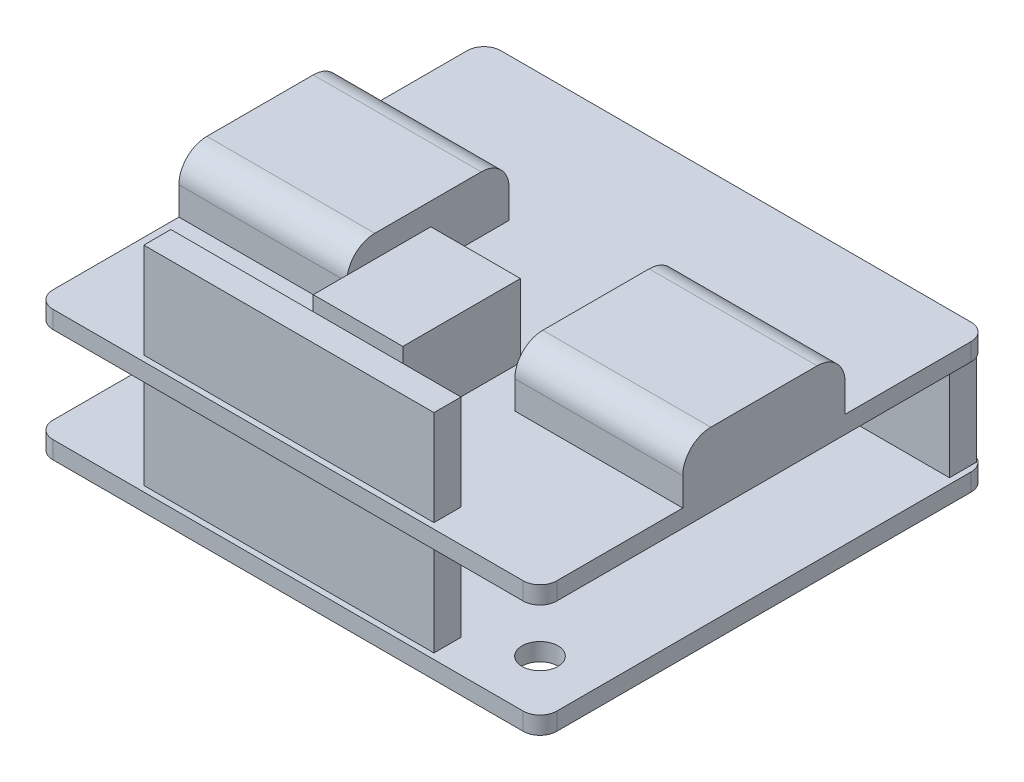
SolidWorks part; units mm, degrees
ref_plane "Front Plane" through (0, 0, 0) normal (0, 0, 1) x (1, 0, 0)
ref_plane "Top Plane" through (0, 0, 0) normal (0, 1, 0) x (1, 0, 0)
ref_plane "Right Plane" through (0, 0, 0) normal (1, 0, 0) x (0, 0, -1)
sketch "Sketch1" plane through (0, 0, 0) normal (0, 1, 0) x (1, 0, 0)
  line L1 (-22.5, -20) -> (22.5, -20)
  line L2 (-22.5, -20) -> (-22.5, 20)
  line L3 (-22.5, 20) -> (22.5, 20)
  line L4 (22.5, -20) -> (22.5, 20)
  line L5 (-22.5, -20) -> (22.5, 20) construction
  line L6 (-22.5, 20) -> (22.5, -20) construction
  point P0 (0, 0)
  dimension "D1" = 45
  dimension "D2" = 40
extrude "Boss-Extrude1" add sketch "Sketch1" along normal blind 1.57
sketch "Sketch2" plane through (0, 1.57, 0) normal (0, 1, 0) x (1, 0, 0)
  line L0 (-13.9, -20) -> (-13.9, 20) construction
  line L1 (21.99, 19.49) -> (-3.92, 19.49)
  line L2 (21.99, 19.49) -> (21.99, 17.08)
  line L3 (21.99, 17.08) -> (-3.92, 17.08)
  line L4 (-3.92, 19.49) -> (-3.92, 17.08)
  line L5 (12.52, -17.08) -> (-13.39, -17.08)
  line L6 (12.52, -17.08) -> (12.52, -19.49)
  line L7 (12.52, -19.49) -> (-13.39, -19.49)
  line L8 (-13.39, -17.08) -> (-13.39, -19.49)
  line L9 (-22.5, -20) -> (22.5, -20) construction
  line L10 (22.5, 20) -> (-22.5, 20) construction
  line L11 (22.5, -20) -> (22.5, 20) construction
  circle A0 centre (17.5, -15) radius 3.2 construction
  dimension "D6" = 6.4
  dimension "D1" = 2.41
  dimension "D2" = 2.41
  dimension "D3" = 25.91
  dimension "D4" = 25.91
  dimension "D5" = 36.4
  dimension "D7" = 5
  dimension "D8" = 5
  dimension "D9" = 0.51
  dimension "D10" = 0.51
  dimension "D11" = 0.51
  dimension "D12" = 0.51
extrude "Boss-Extrude2" add sketch "Sketch2" along normal blind 8.51
sketch "Sketch3" plane through (0, 10.08, 0) normal (0, 1, 0) x (1, 0, 0)
  line L0 (22.5, 20) -> (-22.5, 20) construction
  line L1 (22.5, -20) -> (-22.5, -20)
  line L2 (22.5, -20) -> (22.5, 20)
  line L3 (22.5, 20) -> (-22.5, 20)
  line L4 (-22.5, -20) -> (-22.5, 20)
  dimension "D1" = 45
extrude "Boss-Extrude3" add sketch "Sketch3" along normal blind 1.57
sketch "Sketch4" plane through (0, 11.65, 0) normal (0, 1, 0) x (1, 0, 0)
  line L0 (12.52, -17.08) -> (-13.39, -17.08)
  line L1 (12.52, -17.08) -> (12.52, -19.49)
  line L2 (12.52, -19.49) -> (-13.39, -19.49)
  line L3 (-13.39, -17.08) -> (-13.39, -19.49)
  line L4 (-22.5, -20) -> (22.5, -20) construction
  line L5 (22.5, -20) -> (22.5, 20) construction
  dimension "D1" = 0.51
  dimension "D2" = 2.41
  dimension "D3" = 25.91
  dimension "D4" = 9.98
extrude "Boss-Extrude4" add sketch "Sketch4" along normal blind 8.51
sketch "Sketch5" plane through (0, 11.65, 0) normal (0, 1, 0) x (1, 0, 0)
  line L0 (-22.5, 20) -> (-22.5, -20) construction
  line L1 (-22.5, -7.25) -> (-7.5, -7.25)
  line L2 (-22.5, -7.25) -> (-22.5, 7.25)
  line L3 (-22.5, 7.25) -> (-7.5, 7.25)
  line L4 (-7.5, -7.25) -> (-7.5, 7.25)
  line L5 (-11.088, 0) -> (11.088, 0) construction
  point P6 (-7.5, 0)
  dimension "D1" = 14.5
  dimension "D2" = 15
extrude "Boss-Extrude5" add sketch "Sketch5" along normal blind 5
fillet "Fillet1" radius 2.5 2 edges at (-15, 16.65, -7.25) (-15, 16.65, 7.25)
mirror "Mirror1" about plane through (0, 0, 0) normal (1, 0, 0) of "Fillet1", "Boss-Extrude5"
sketch "Sketch6" plane through (0, 11.65, 0) normal (0, 1, 0) x (1, 0, 0)
  line L0 (0, -11.088) -> (0, 11.088) construction
  line L1 (-4, -13.75) -> (4, -13.75)
  line L2 (-4, -13.75) -> (-4, -3.25)
  line L3 (-4, -3.25) -> (4, -3.25)
  line L4 (4, -13.75) -> (4, -3.25)
  line L5 (-11.088, 0) -> (11.088, 0) construction
  point P4 (0, -13.75)
  point P7 (-4, -8.5)
  dimension "D1" = 8
  dimension "D2" = 10.5
  dimension "D3" = 8.5
extrude "Boss-Extrude6" add sketch "Sketch6" along normal blind 6.5
sketch "Sketch7" plane through (0, 1.57, 0) normal (0, 1, 0) x (1, 0, 0)
  line L0 (-22.5, -20) -> (22.5, -20) construction
  line L1 (22.5, -20) -> (22.5, -7.25) construction
  line L2 (-22.5, 20) -> (-22.5, 7.25) construction
  line L3 (22.5, 20) -> (-22.5, 20) construction
  circle A0 centre (17.5, -15) radius 1.6
  circle A1 centre (-17.5, 15) radius 1.6
  point P10 (0, 0)
  point P12 (-17.2804, 17.0043)
  dimension "D3" = 3.2
  dimension "D6" = 3.2
  dimension "D1" = 5
  dimension "D2" = 5
  dimension "D4" = 5
  dimension "D5" = 5
extrude "Cut-Extrude1" cut sketch "Sketch7" against normal up to next
fillet "Fillet2" radius 1.5 4 edges at (-22.5, 0.785, -20) (-22.5, 0.785, 20) (22.5, 0.785, 20) (22.5, 0.785, -20)
fillet "Fillet3" radius 1.5 4 edges at (-22.5, 10.865, -20) (22.5, 10.865, 20) (22.5, 10.865, -20) (-22.5, 10.865, 20)
